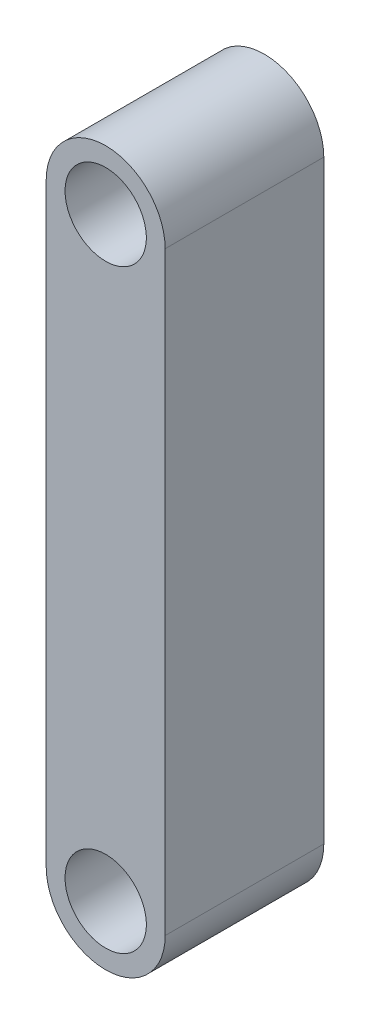
SolidWorks part; units mm, degrees
ref_plane "Front Plane" through (0, 0, 0) normal (0, 0, 1) x (1, 0, 0)
ref_plane "Top Plane" through (0, 0, 0) normal (0, 1, 0) x (1, 0, 0)
ref_plane "Right Plane" through (0, 0, 0) normal (1, 0, 0) x (0, 0, -1)
sketch "Sketch1" plane through (0, 0, 0) normal (0, 0, 1) x (1, 0, 0)
  line L2 (-3, 15) -> (-3, -15)
  line L4 (3, 15) -> (3, -15)
  arc A0 (3, 15) -> (-3, 15) centre (0, 15) ccw
  arc A1 (-3, -15) -> (3, -15) centre (0, -15) ccw
  point P7 (-3, 0)
  point P11 (3, 0)
  dimension "D2" = 6
  dimension "D1" = 30
extrude "Boss-Extrude1" add sketch "Sketch1" along normal blind 8 contours A0 L2 A1 L4
hole_wizard "Ø4.0 mm Dowel Holes1" positions "Sketch2" profile "Sketch3" hole size "Ø4.0" standard "ISO" end condition through all
sketch "Sketch2" plane through (0, 0, 0) normal (0, 0, -1) x (-1, 0, 0)
  point P0 (0, 15)
sketch "Sketch3" plane through (0, 15, 0) normal (1, 0, 0) x (0, 1, 0)
  line L0 (0, 0) -> (0, 8)
  line L1 (0, 8) -> (2.05, 8)
  line L2 (2.05, 8) -> (2.05, 0)
  line L5 (2.05, 0) -> (0, 0)
  line L11 (0, -6.35) -> (0, 107.95) construction
  dimension "Thru Hole Dia." = 4.1
  dimension "Thru Hole Depth" = 8
mirror "Mirror1" about plane through (0, 0, 0) normal (0, 1, 0) of "Ø4.0 mm Dowel Holes1"
